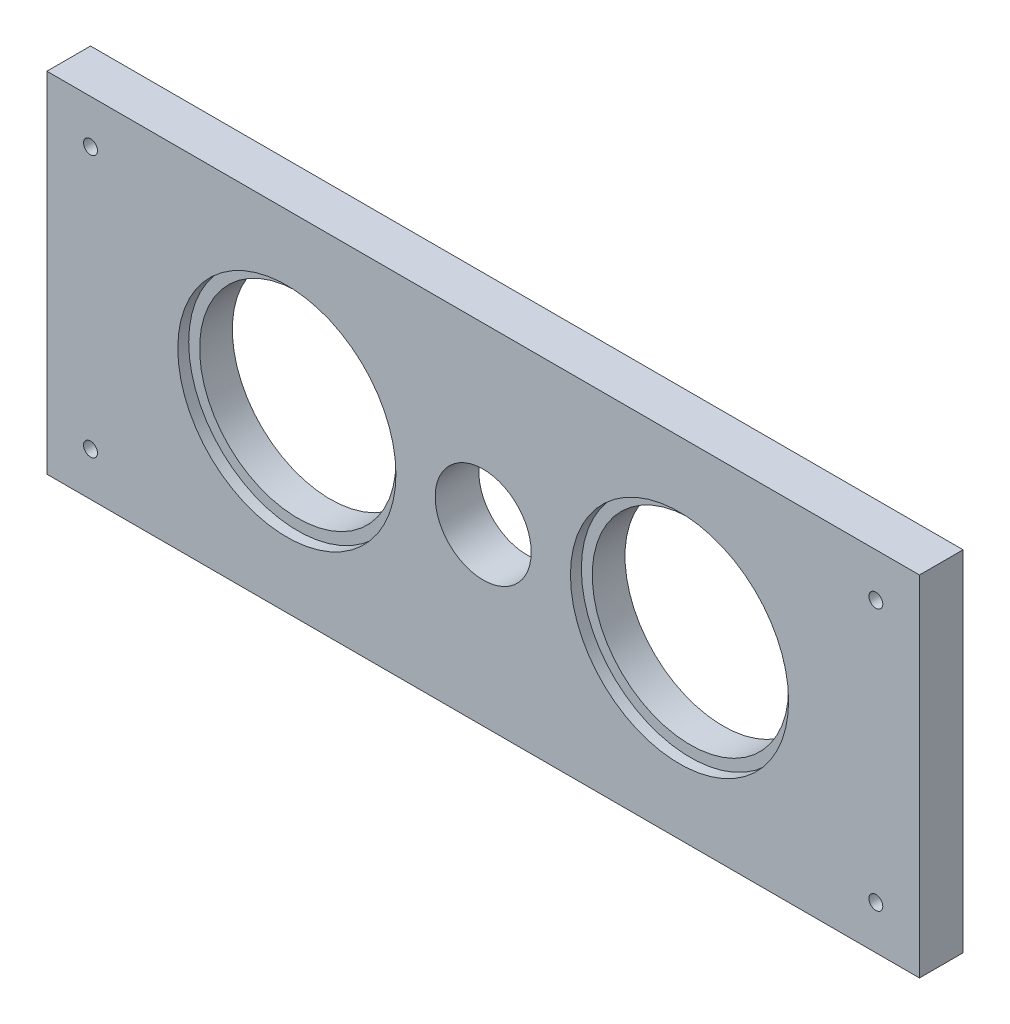
SolidWorks part; units mm, degrees
ref_plane "front" through (0, 0, 0) normal (0, 0, 1) x (1, 0, 0)
ref_plane "top" through (0, 0, 0) normal (0, 1, 0) x (1, 0, 0)
ref_plane "right" through (0, 0, 0) normal (1, 0, 0) x (0, 0, -1)
sketch "Sketch3" plane through (0, 0, 0) normal (0, 0, 1) x (1, 0, 0)
  line L0 (0, 50.8) -> (0, 65.5091) construction
  line L1 (127, 0) -> (104.6696, 0) construction
  line L2 (-127, 50.8) -> (127, 50.8)
  line L3 (-127, 50.8) -> (-127, -50.8)
  line L4 (-127, -50.8) -> (127, -50.8)
  line L5 (127, 50.8) -> (127, -50.8)
  circle A0 centre (57.15, 0) radius 28.575
  circle A1 centre (87.4397, -50.8) radius 3.8017
  circle A2 centre (-23.5712, -93.4212) radius 2.54
  circle A3 centre (114.3, 38.1) radius 2.0193
  circle A4 centre (114.3, -38.1) radius 2.0193
  circle A5 centre (57.15, 0) radius 31.75
  circle A6 centre (-57.15, 0) radius 31.75
  circle A7 centre (-114.3, -38.1) radius 2.0193
  circle A8 centre (-114.3, 38.1) radius 2.0193
  circle A9 centre (-57.15, 0) radius 28.575
  circle A10 centre (0, 0) radius 13.9773
  circle A11 centre (0, -69.85) radius 19.05
  circle A12 centre (23.5712, -46.2788) radius 2.54
  circle A13 centre (23.5712, -93.4212) radius 2.54
  circle A14 centre (34.925, 31.75) radius 2.2363
  circle A15 centre (34.925, -31.75) radius 2.0127
  circle A16 centre (87.4397, -32.1836) radius 2.2363
  circle A17 centre (87.4397, 32.893) radius 2.0127
  circle A18 centre (-23.5712, -46.2788) radius 2.54
  dimension "D1" = 57.15
  dimension "D2" = 63.5
  dimension "D3" = 4.0386
  dimension "D17" = 38.1
  dimension "D18" = 5.08
  dimension "D4" = 101.6
  dimension "D5" = 254
  dimension "D6" = 57.15
  dimension "D7" = 114.3
  dimension "D8" = 38.1
  dimension "D9" = 38.1
  dimension "D10" = 50.8
  dimension "D11" = 31.75
  dimension "D12" = 34.925
  dimension "D13" = 31.75
  dimension "D14" = 23.5712
  dimension "D15" = 23.5712
  dimension "D16" = 23.5712
  dimension "D19" = 69.85
sketch "Sketch4" plane through (0, 0, 0) normal (0, 0, 1) x (1, 0, 0)
  line L0 (-127, 50.8) -> (127, 50.8) construction
  line L1 (-127, 50.8) -> (-127, -50.8) construction
  line L2 (-127, -50.8) -> (127, -50.8) construction
  line L3 (127, 50.8) -> (127, -50.8) construction
  line L4 (-127, 50.8) -> (127, 50.8)
  line L5 (-127, 50.8) -> (-127, -50.8)
  line L6 (-127, -50.8) -> (127, -50.8)
  line L7 (127, 50.8) -> (127, -50.8)
extrude "Base-Extrude" add sketch "Sketch4" against normal blind 12.7
sketch "Sketch5" plane through (0, 0, 0) normal (0, 0, 1) x (1, 0, 0)
  circle A0 centre (-57.15, 0) radius 28.575 construction
  circle A1 centre (57.15, 0) radius 28.575 construction
  circle A2 centre (-57.15, 0) radius 28.575
  circle A3 centre (57.15, 0) radius 28.575
  circle A4 centre (0, 0) radius 13.9773 construction
  circle A5 centre (0, 0) radius 13.9773
extrude "Cut-Extrude1" cut sketch "Sketch5" against normal blind 12.7
sketch "Sketch6" plane through (0, 0, 0) normal (0, 0, 1) x (1, 0, 0)
  circle A0 centre (-57.15, 0) radius 31.75 construction
  circle A1 centre (57.15, 0) radius 31.75 construction
  circle A2 centre (-57.15, 0) radius 31.75
  circle A3 centre (57.15, 0) radius 31.75
extrude "Cut-Extrude2" cut sketch "Sketch6" against normal blind 3.175
sketch "Sketch7" plane through (0, 0, 0) normal (0, 0, 1) x (1, 0, 0)
  circle A0 centre (-114.3, -38.1) radius 2.0193 construction
  circle A1 centre (-114.3, 38.1) radius 2.0193 construction
  circle A4 centre (114.3, -38.1) radius 2.0193 construction
  circle A5 centre (114.3, 38.1) radius 2.0193 construction
  circle A6 centre (-114.3, -38.1) radius 2.0193
  circle A7 centre (-114.3, 38.1) radius 2.0193
  circle A10 centre (114.3, -38.1) radius 2.0193
  circle A11 centre (114.3, 38.1) radius 2.0193
extrude "Cut-Extrude3" cut sketch "Sketch7" against normal blind 25.4
